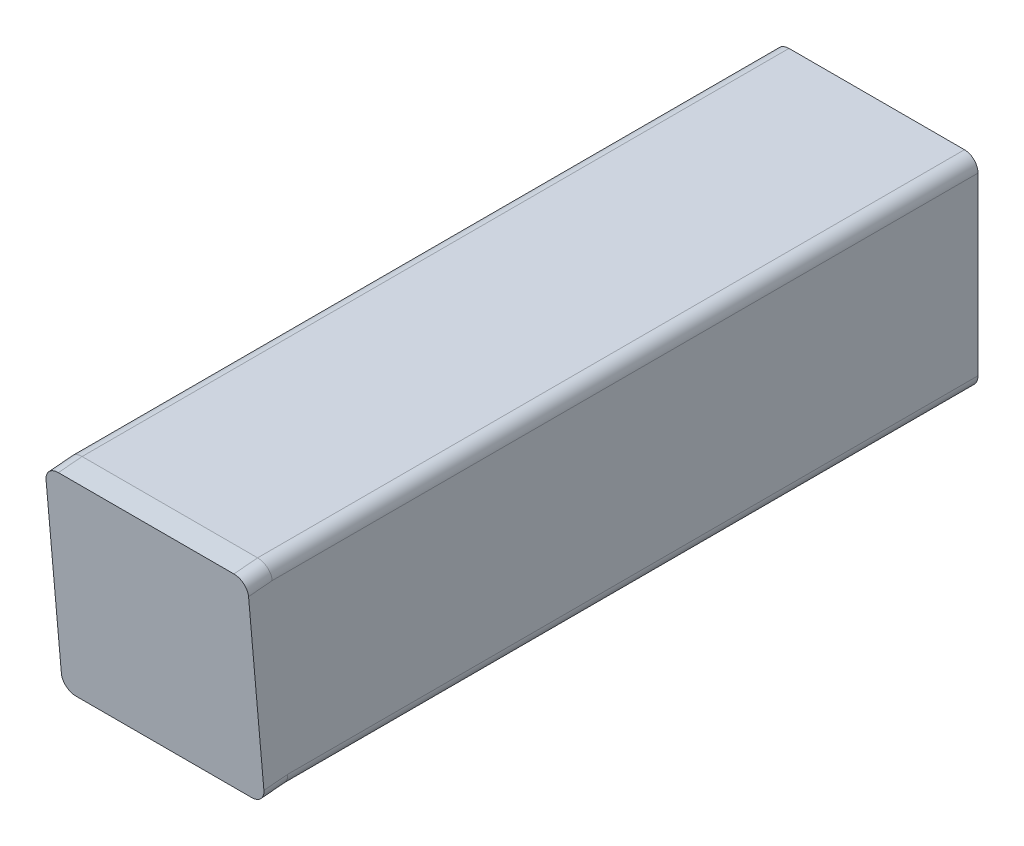
SolidWorks part; units mm, degrees
material "ASTM A500 Grade B Steel"
ref_plane "Front Plane" through (0, 0, 0) normal (0, 0, 1) x (1, 0, 0)
ref_plane "Top Plane" through (0, 0, 0) normal (0, 1, 0) x (1, 0, 0)
ref_plane "Right Plane" through (0, 0, 0) normal (1, 0, 0) x (0, 0, -1)
sketch "Sketch1" plane through (0, 0, 0) normal (0, 0, 1) x (1, 0, 0)
  line L0 (5.3086, -2.7686) -> (32.7914, -2.7686)
  line L1 (2.54, 0) -> (35.56, 0)
  line L2 (0, -2.54) -> (0, -35.56)
  line L3 (2.54, -38.1) -> (35.56, -38.1)
  line L4 (38.1, -2.54) -> (38.1, -35.56)
  line L5 (35.3314, -5.3086) -> (35.3314, -32.7914)
  line L6 (5.3086, -35.3314) -> (32.7914, -35.3314)
  line L7 (2.7686, -5.3086) -> (2.7686, -32.7914)
  line L8 (0, 0) -> (0, -38.1) construction
  line L9 (0, -38.1) -> (38.1, -38.1) construction
  line L10 (38.1, 0) -> (38.1, -38.1) construction
  line L11 (2.7686, -2.7686) -> (2.7686, -35.3314) construction
  line L12 (2.7686, -35.3314) -> (35.3314, -35.3314) construction
  line L13 (35.3314, -2.7686) -> (35.3314, -35.3314) construction
  line L14 (2.7686, -2.7686) -> (35.3314, -2.7686) construction
  line L15 (0, 0) -> (38.1, 0) construction
  arc A0 (0, -35.56) -> (2.54, -38.1) centre (2.54, -35.56) ccw
  arc A1 (38.1, -35.56) -> (35.56, -38.1) centre (35.56, -35.56) cw
  arc A2 (2.7686, -32.7914) -> (5.3086, -35.3314) centre (5.3086, -32.7914) ccw
  arc A3 (32.7914, -35.3314) -> (35.3314, -32.7914) centre (32.7914, -32.7914) ccw
  arc A4 (35.3314, -5.3086) -> (32.7914, -2.7686) centre (32.7914, -5.3086) ccw
  arc A5 (38.1, -2.54) -> (35.56, 0) centre (35.56, -2.54) ccw
  arc A6 (0, -2.54) -> (2.54, 0) centre (2.54, -2.54) cw
  arc A7 (5.3086, -2.7686) -> (2.7686, -5.3086) centre (5.3086, -5.3086) ccw
  point P12 (0, -38.1)
  dimension "D4" = 2.54
  dimension "D3" = 2.7686
extrude "Boss-Extrude1" add sketch "Sketch1" along normal blind 133
sketch "Sketch2" plane through (38.1, 0, 0) normal (1, 0, 0) x (0, 0, -1)
  line L0 (-133, 0) -> (-129.6667, -38.1)
  line L1 (-133, -38.1) -> (0, -38.1) construction
  line L2 (-129.6667, -38.1) -> (-133, -38.1)
  line L3 (-133, -38.1) -> (-133, 0)
  dimension "D1" = 5
extrude "Cut-Extrude1" cut sketch "Sketch2" against normal through all
sketch "Sketch3" plane through (0, -11.5476, 131.9897) normal (0, -0.0872, 0.9962) x (1, 0, 0)
  line L4 (2.54, -26.6538) -> (35.56, -26.6538)
  line L5 (38.1, -24.1041) -> (38.1, 9.042)
  line L6 (35.56, 11.5917) -> (2.54, 11.5917)
  line L7 (0, 9.042) -> (0, -24.1041)
  line L8 (2.54, -26.6538) -> (35.56, -26.6538)
  line L9 (38.1, -24.1041) -> (38.1, 9.042)
  line L10 (35.56, 11.5917) -> (2.54, 11.5917)
  line L11 (0, 9.042) -> (0, -24.1041)
  ellipse E4 centre (35.56, -24.1041) end of major axis (35.56, -26.6538) minor radius 2.54 (35.56, -26.6538) -> (38.1, -24.1041) ccw
  ellipse E5 centre (35.56, 9.042) end of major axis (35.56, 6.4923) minor radius 2.54 (38.1, 9.042) -> (35.56, 11.5917) ccw
  ellipse E6 centre (2.54, 9.042) end of major axis (2.54, 11.5917) minor radius 2.54 (2.54, 11.5917) -> (0, 9.042) ccw
  ellipse E7 centre (2.54, -24.1041) end of major axis (2.54, -26.6538) minor radius 2.54 (0, -24.1041) -> (2.54, -26.6538) ccw
  ellipse E8 centre (35.56, -24.1041) end of major axis (35.56, -26.6538) minor radius 2.54 (35.56, -26.6538) -> (38.1, -24.1041) ccw
  ellipse E9 centre (35.56, 9.042) end of major axis (35.56, 6.4923) minor radius 2.54 (38.1, 9.042) -> (35.56, 11.5917) ccw
  ellipse E10 centre (2.54, 9.042) end of major axis (2.54, 11.5917) minor radius 2.54 (2.54, 11.5917) -> (0, 9.042) ccw
  ellipse E11 centre (2.54, -24.1041) end of major axis (2.54, -26.6538) minor radius 2.54 (0, -24.1041) -> (2.54, -26.6538) ccw
  dimension "D1" = 0
extrude "Boss-Extrude2" add sketch "Sketch3" along normal up to surface (4.4808 mm away)
